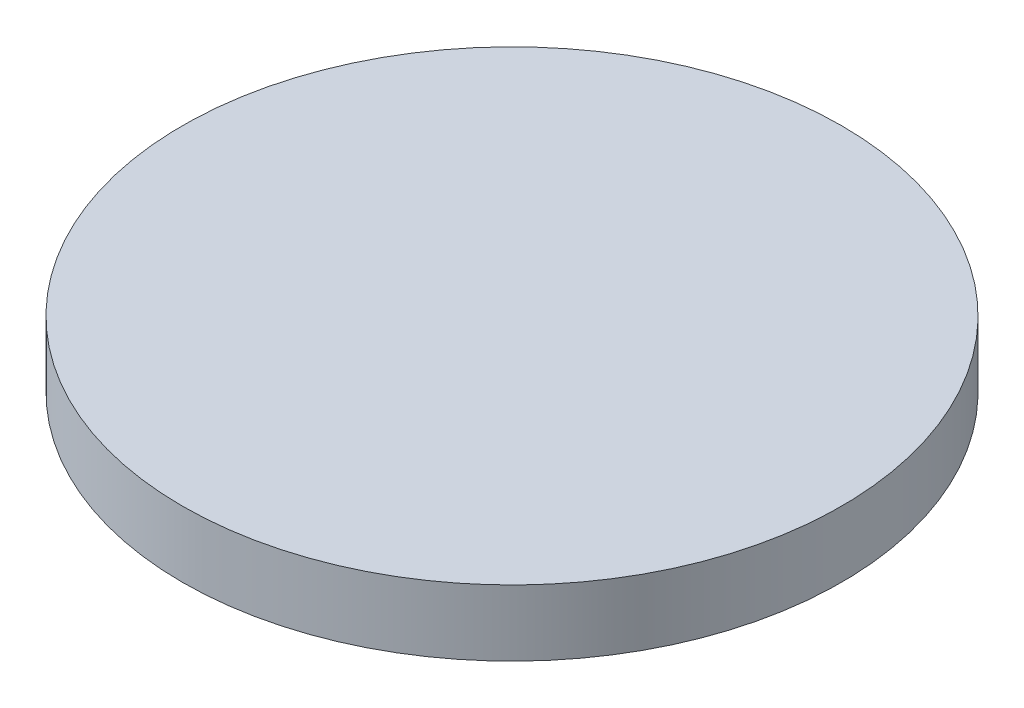
SolidWorks part; units mm, degrees
ref_plane "Front Plane" through (0, 0, 0) normal (0, 0, 1) x (1, 0, 0)
ref_plane "Top Plane" through (0, 0, 0) normal (0, 1, 0) x (1, 0, 0)
ref_plane "Right Plane" through (0, 0, 0) normal (1, 0, 0) x (0, 0, -1)
sketch "Sketch1" plane through (0, 0, 0) normal (0, 0, 1) x (1, 0, 0)
  line L0 (9.906, 1.9837) -> (0, 1.9837)
  line L1 (0, 1.9837) -> (0, 0)
  line L2 (0, 0) -> (9.906, 0)
  line L3 (9.906, 0) -> (9.906, 1.9837)
  line L4 (0, 1.9837) -> (0, 0) construction
  dimension "D1" = 1.9837
  dimension "D2" = 9.906
revolve "Revolve1" add sketch "Sketch1" angle 360 about L4
